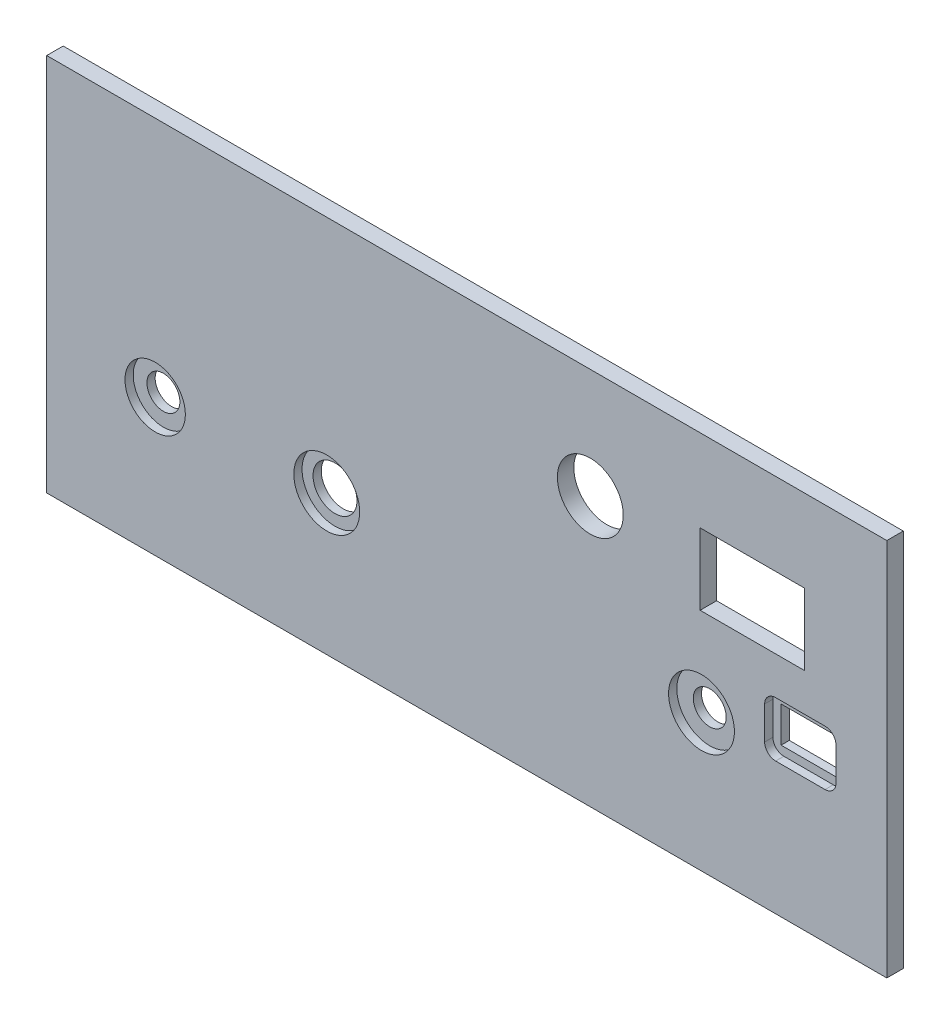
SolidWorks part; units mm, degrees
ref_plane "Ön Düzlem" through (0, 0, 0) normal (0, 0, 1) x (1, 0, 0)
ref_plane "Üst Düzlem" through (0, 0, 0) normal (0, 1, 0) x (1, 0, 0)
ref_plane "Sağ Düzlem" through (0, 0, 0) normal (1, 0, 0) x (0, 0, -1)
sketch "Çizim1" plane through (0, 0, 0) normal (0, 0, 1) x (1, 0, 0)
  line L1 (0, 0) -> (-153, 0)
  line L2 (0, 0) -> (0, 69)
  line L3 (0, 69) -> (-153, 69)
  line L4 (-153, 0) -> (-153, 69)
  dimension "D1" = 153
  dimension "D2" = 69
extrude "Yükseklik-Ekstrüzyon1" add sketch "Çizim1" along normal blind 3
sketch "Çizim2" plane through (0, 0, 3) normal (0, 0, 1) x (1, 0, 0)
  line L0 (-153, 69) -> (-153, 0) construction
  line L1 (-153, 0) -> (0, 0) construction
  line L2 (0, 0) -> (0, 69) construction
  line L3 (0, 69) -> (-153, 69) construction
  line L5 (-34, 54) -> (-15, 54)
  line L6 (-34, 54) -> (-34, 41)
  line L7 (-34, 41) -> (-15, 41)
  line L8 (-15, 54) -> (-15, 41)
  circle A0 centre (-133.25, 25) radius 3
  circle A1 centre (-102, 25.5) radius 4
  circle A2 centre (-33.75, 25) radius 3
  circle A3 centre (-54, 49) radius 6
  dimension "D1" = 6
  dimension "D6" = 8
  dimension "D7" = 6
  dimension "D10" = 12
  dimension "D2" = 19.75
  dimension "D3" = 25
  dimension "D4" = 25.5
  dimension "D5" = 51
  dimension "D8" = 25
  dimension "D9" = 33.75
  dimension "D11" = 54
  dimension "D12" = 20
  dimension "D13" = 13
  dimension "D14" = 19
  dimension "D15" = 15
  dimension "D16" = 15
extrude "Kes-Ekstrüzyon1" cut sketch "Çizim2" against normal blind 3
sketch "Çizim4" plane through (0, 0, 3) normal (0, 0, 1) x (1, 0, 0)
  circle A0 centre (-133.25, 25) radius 5.5
  circle A1 centre (-102, 25.5) radius 6
  circle A2 centre (-33.75, 25) radius 6
  dimension "D1" = 11
  dimension "D2" = 12
  dimension "D3" = 12
extrude "Kes-Ekstrüzyon2" cut sketch "Çizim4" against normal blind 1.5
sketch "Çizim5" plane through (0, 0, 3) normal (0, 0, 1) x (1, 0, 0)
  line L0 (0, 0) -> (0, 69) construction
  line L1 (-22.25, 34.1) -> (-9.25, 34.1)
  line L2 (-22.25, 34.1) -> (-22.25, 24.1)
  line L3 (-22.25, 24.1) -> (-9.25, 24.1)
  line L4 (-9.25, 34.1) -> (-9.25, 24.1)
  line L5 (-153, 0) -> (0, 0) construction
  dimension "D1" = 13
  dimension "D2" = 10
  dimension "D3" = 9.25
  dimension "D4" = 24.1
extrude "Kes-Ekstrüzyon4" cut sketch "Çizim5" against normal blind 1.5
sketch "Çizim7" plane through (0, 0, 1.5) normal (0, 0, 1) x (1, 0, 0)
  line L0 (-22.25, 34.1) -> (-22.25, 24.1) construction
  line L1 (-20.75, 32.1) -> (-10.75, 32.1)
  line L2 (-20.75, 32.1) -> (-20.75, 25.6)
  line L3 (-20.75, 25.6) -> (-10.75, 25.6)
  line L4 (-10.75, 32.1) -> (-10.75, 25.6)
  line L5 (-9.25, 24.1) -> (-9.25, 34.1) construction
  line L6 (-9.25, 34.1) -> (-22.25, 34.1) construction
  dimension "D1" = 1.5
  dimension "D2" = 1.5
  dimension "D3" = 2
  dimension "D4" = 1.5
extrude "Kes-Ekstrüzyon5" cut sketch "Çizim7" against normal blind 1.5
fillet "Radyus1" radius 2 4 edges at (-9.25, 24.1, 2.25) (-22.25, 24.1, 2.25) (-22.25, 34.1, 2.25) (-9.25, 34.1, 2.25)
